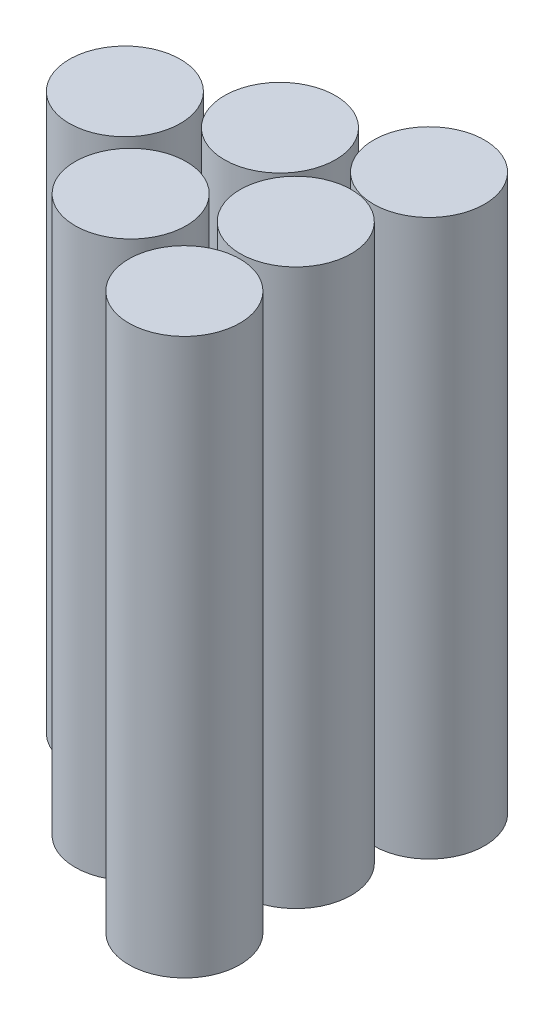
SolidWorks part; units mm, degrees
ref_plane "Front Plane" through (0, 0, 0) normal (0, 0, 1) x (1, 0, 0)
ref_plane "Top Plane" through (0, 0, 0) normal (0, 1, 0) x (1, 0, 0)
ref_plane "Right Plane" through (0, 0, 0) normal (1, 0, 0) x (0, 0, -1)
sketch "Sketch1" plane through (0, 0, 0) normal (0, 1, 0) x (1, 0, 0)
  circle A0 centre (0, 0) radius 0.125
  circle A1 centre (-0.2007, 0.1652) radius 0.125
  circle A2 centre (0.0535, 0.2464) radius 0.125
  circle A3 centre (-0.4459, 0.0615) radius 0.125
  circle A4 centre (-0.2402, -0.1312) radius 0.125
  circle A5 centre (0.01, -0.2605) radius 0.125
  point P13 (0.0535, 0.2464)
  point P14 (0.2585, 0.0819)
  point P15 (-0.2007, 0.1652)
  point P16 (-0.2392, -0.0943)
  point P17 (-0.0352, -0.2567)
  point P18 (-0.4459, 0.0615)
  point P19 (0.01, -0.2605)
  point P20 (-0.2402, -0.1312)
  dimension "D1" = 0.25
extrude "Boss-Extrude1" add sketch "Sketch1" along normal blind 1.25
